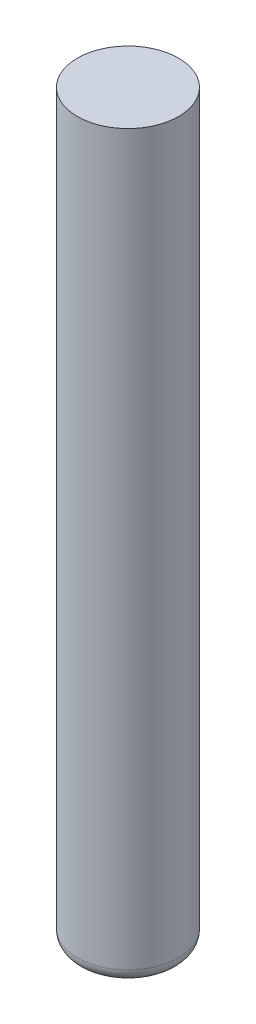
SolidWorks part; units mm, degrees
ref_plane "Front Plane" through (0, 0, 0) normal (0, 0, 1) x (1, 0, 0)
ref_plane "Top Plane" through (0, 0, 0) normal (0, 1, 0) x (1, 0, 0)
ref_plane "Right Plane" through (0, 0, 0) normal (1, 0, 0) x (0, 0, -1)
sketch "Sketch1" plane through (0, 0, 0) normal (0, 1, 0) x (1, 0, 0)
  circle A0 centre (0, 0) radius 15
  dimension "D1" = 30
extrude "Boss-Extrude1" add sketch "Sketch1" along normal blind 220
fillet "Fillet1" radius 4 1 edges at (0, 0, 15)
